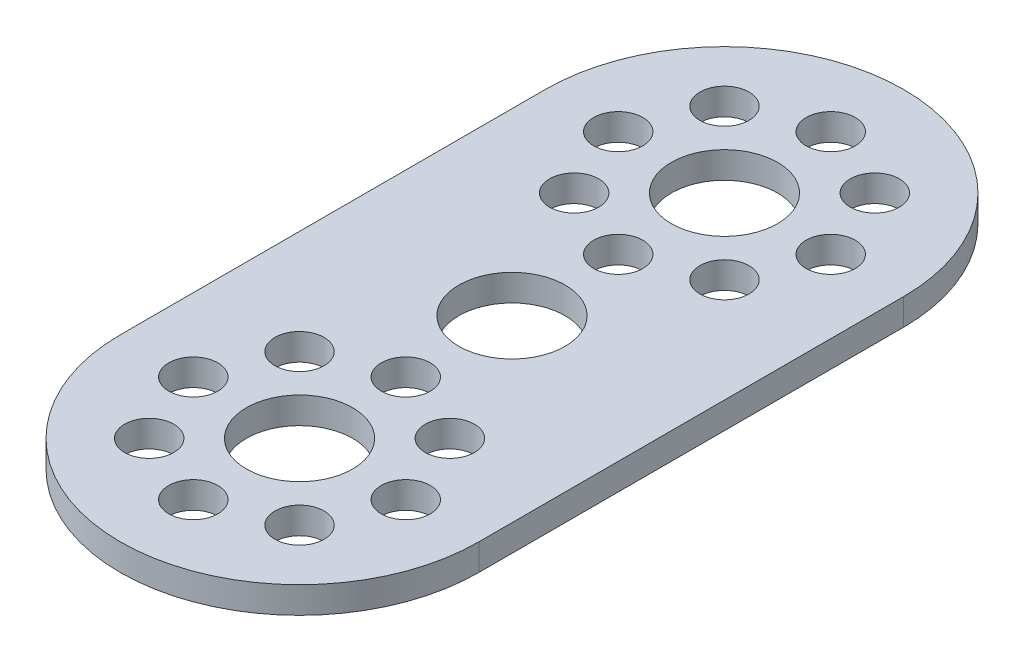
SolidWorks part; units mm, degrees
material "5052-H32"
ref_plane "Front Plane" through (0, 0, 0) normal (0, 0, 1) x (1, 0, 0)
ref_plane "Top Plane" through (0, 0, 0) normal (0, 1, 0) x (1, 0, 0)
ref_plane "Right Plane" through (0, 0, 0) normal (1, 0, 0) x (0, 0, -1)
sketch "Sketch1" plane through (0, 0, 0) normal (0, 1, 0) x (1, 0, 0)
  line L2 (-13.5, 16) -> (-13.5, -16)
  line L4 (13.5, 16) -> (13.5, -16)
  line L5 (-13.5, 32) -> (13.5, -32) construction
  line L6 (-13.5, -32) -> (13.5, 32) construction
  arc A0 (-13.5, -16) -> (13.5, -16) centre (0, -16) ccw
  arc A2 (13.5, 16) -> (-13.5, 16) centre (0, 16) ccw
  point P0 (0, 0)
  dimension "D1" = 27
  dimension "D2" = 64
extrude "Extrude1" add sketch "Sketch1" along normal blind 2
sketch "Sketch2" plane through (0, 2, 0) normal (0, 1, 0) x (1, 0, 0)
  line L0 (0, -34.8298) -> (0, 34.3185) construction
  line L1 (-20.0671, 0) -> (21.473, 0) construction
  circle A0 centre (0, 0) radius 4
  circle B0 centre (8, -16) radius 1.85
  circle B1 centre (0, -24) radius 1.85
  circle B2 centre (0, -16) radius 4
  circle B3 centre (0, -8) radius 1.85
  circle B4 centre (-5.66, -10.34) radius 1.85
  circle B5 centre (-5.66, -21.66) radius 1.85
  circle B6 centre (-8, -16) radius 1.85
  circle B7 centre (5.66, -10.34) radius 1.85
  circle B8 centre (5.66, -21.66) radius 1.85
  circle B9 centre (8, 16) radius 1.85
  circle B10 centre (0, 8) radius 1.85
  circle B11 centre (0, 16) radius 4
  circle B12 centre (0, 24) radius 1.85
  circle B13 centre (-5.66, 21.66) radius 1.85
  circle B14 centre (-5.66, 10.34) radius 1.85
  circle B15 centre (-8, 16) radius 1.85
  circle B16 centre (5.66, 21.66) radius 1.85
  circle B17 centre (5.66, 10.34) radius 1.85
  dimension "D1" = 16
  dimension "D2" = 16
sketch_block_instance "TETRIX 8 hole Pattern-1"
sketch_block "TETRIX 8 hole Pattern"
sketch_block_instance "TETRIX 8 hole Pattern-2"
extrude "Extrude2" cut sketch "Sketch2" against normal blind 2
